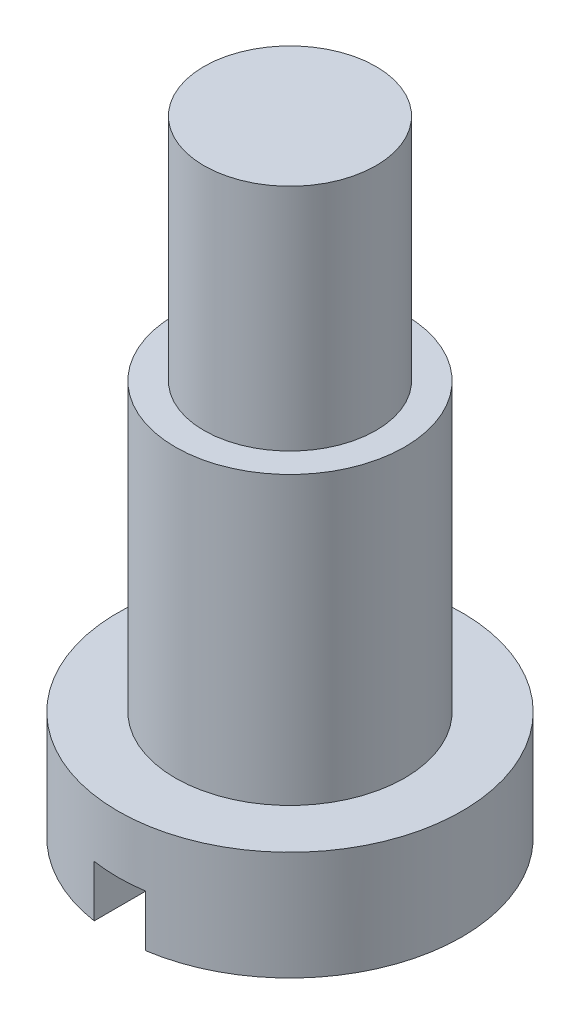
SolidWorks part; units mm, degrees
ref_plane "Front Plane" through (0, 0, 0) normal (0, 0, 1) x (1, 0, 0)
ref_plane "Top Plane" through (0, 0, 0) normal (0, 1, 0) x (1, 0, 0)
ref_plane "Right Plane" through (0, 0, 0) normal (1, 0, 0) x (0, 0, -1)
other "Configuration Table"
sketch "草图1" plane through (0, 0, 0) normal (0, 1, 0) x (1, 0, 0)
  circle A0 centre (0, 0) radius 6
  dimension "D1" = 12
extrude "凸台-拉伸1" add sketch "草图1" along normal blind 3.8
sketch "草图2" plane through (0, 3.8, 0) normal (0, 1, 0) x (1, 0, 0)
  circle A0 centre (0, 0) radius 4
  dimension "D1" = 8
extrude "凸台-拉伸2" add sketch "草图2" along normal blind 10
sketch "草图3" plane through (0, 13.8, 0) normal (0, 1, 0) x (1, 0, 0)
  circle A0 centre (0, 0) radius 3
  dimension "D1" = 6
extrude "凸台-拉伸3" add sketch "草图3" along normal blind 8
sketch "草图4" plane through (0, 0, 0) normal (0, -1, 0) x (1, 0, 0)
  line L1 (-0.9, 6.9605) -> (0.9, 6.9605)
  line L2 (-0.9, 6.9605) -> (-0.9, -6.9605)
  line L3 (-0.9, -6.9605) -> (0.9, -6.9605)
  line L4 (0.9, 6.9605) -> (0.9, -6.9605)
  line L5 (-0.9, 6.9605) -> (0.9, -6.9605) construction
  line L6 (-0.9, -6.9605) -> (0.9, 6.9605) construction
  point P0 (0, 0)
extrude "切除-拉伸1" cut sketch "草图4" against normal blind 1.8
